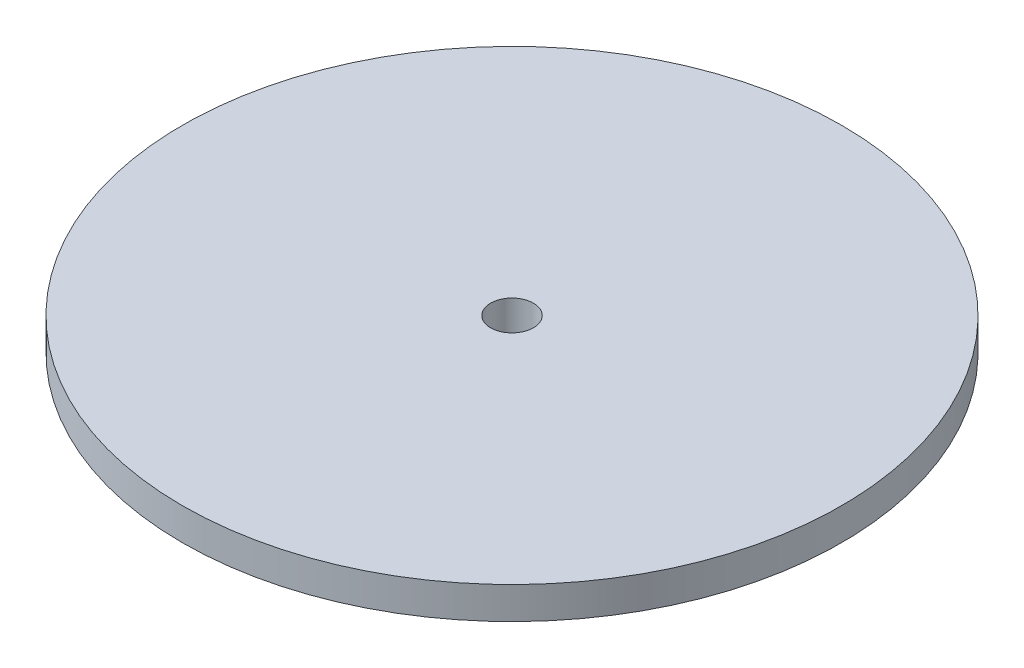
SolidWorks part; units mm, degrees
ref_plane "Front Plane" through (0, 0, 0) normal (0, 0, 1) x (1, 0, 0)
ref_plane "Top Plane" through (0, 0, 0) normal (0, 1, 0) x (1, 0, 0)
ref_plane "Right Plane" through (0, 0, 0) normal (1, 0, 0) x (0, 0, -1)
sketch "Sketch1" plane through (0, 0, 0) normal (0, 1, 0) x (1, 0, 0)
  circle A0 centre (0, 0) radius 30.8
  circle A1 centre (0, 0) radius 2
  dimension "D1" = 61.6
  dimension "D2" = 4
extrude "Boss-Extrude1" add sketch "Sketch1" along normal blind 3
